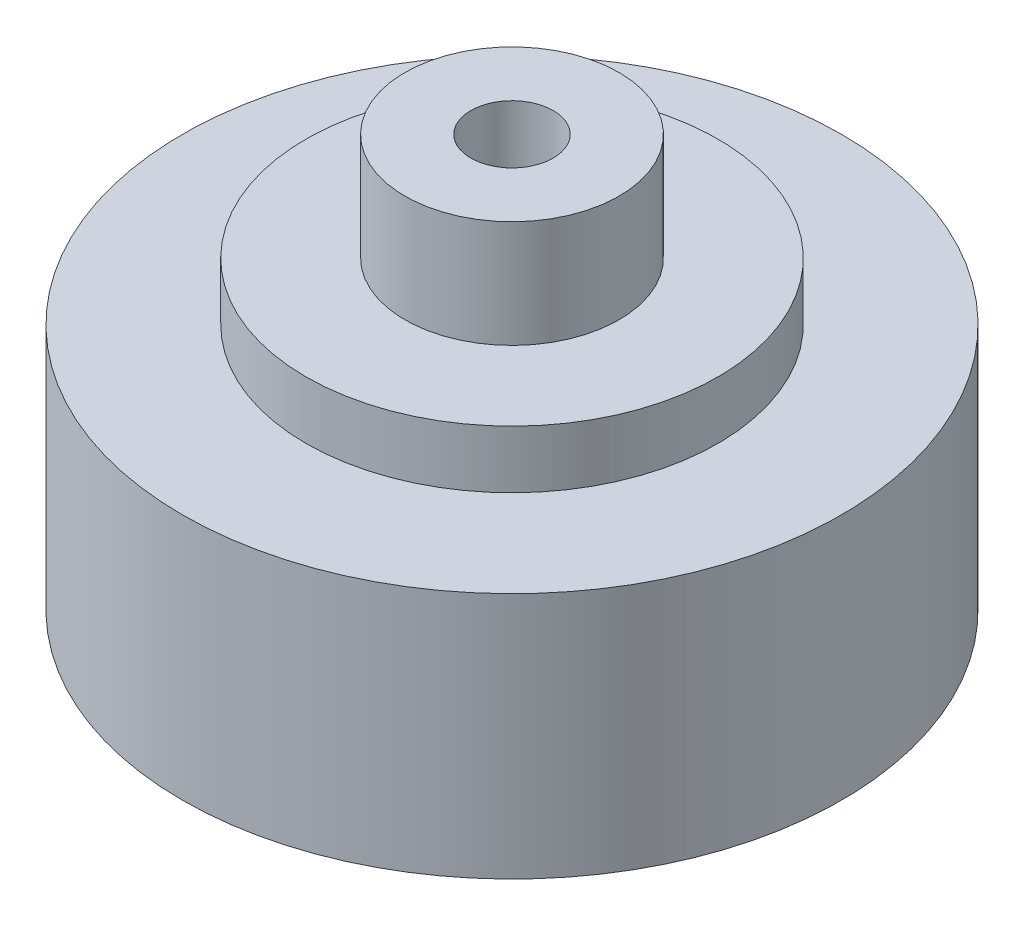
SolidWorks part; units mm, degrees
ref_plane "Front Plane" through (0, 0, 0) normal (0, 0, 1) x (1, 0, 0)
ref_plane "Top Plane" through (0, 0, 0) normal (0, 1, 0) x (1, 0, 0)
ref_plane "Right Plane" through (0, 0, 0) normal (1, 0, 0) x (0, 0, -1)
sketch "Sketch1" plane through (0, 0, 0) normal (0, 1, 0) x (1, 0, 0)
  circle A0 centre (0, 0) radius 40
  dimension "D1" = 80
extrude "Boss-Extrude1" add sketch "Sketch1" along normal blind 30
sketch "Sketch2" plane through (0, 30, 0) normal (0, 1, 0) x (1, 0, 0)
  circle A0 centre (0, 0) radius 25
  dimension "D1" = 50
extrude "Boss-Extrude3" add sketch "Sketch2" along normal blind 7 separate body
sketch "Sketch3" plane through (0, 37, 0) normal (0, 1, 0) x (1, 0, 0)
  circle A0 centre (0, 0) radius 13
  dimension "D1" = 26
extrude "Boss-Extrude4" add sketch "Sketch3" along normal blind 13
sketch "Sketch4" plane through (0, 0, 0) normal (0, -1, 0) x (1, 0, 0)
  circle A0 centre (0, 0) radius 5
  dimension "D1" = 10
extrude "Cut-Extrude2" cut sketch "Sketch4" against normal blind 50
